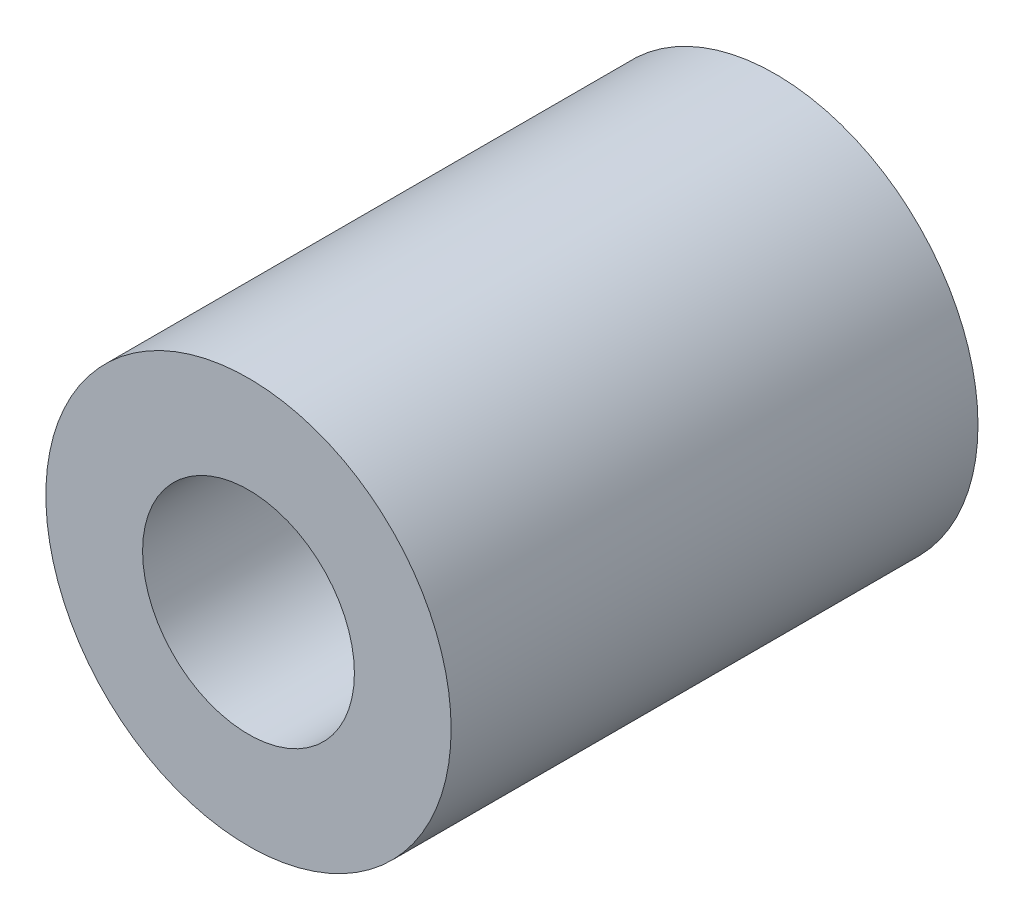
SolidWorks part; units mm, degrees
material "6061-T6 (SS)"
ref_plane "Front Plane" through (0, 0, 0) normal (0, 0, 1) x (1, 0, 0)
ref_plane "Top Plane" through (0, 0, 0) normal (0, 1, 0) x (1, 0, 0)
ref_plane "Right Plane" through (0, 0, 0) normal (1, 0, 0) x (0, 0, -1)
sketch "Sketch1" plane through (0, 0, 0) normal (0, 0, 1) x (1, 0, 0)
  circle A0 centre (0, 0) radius 4.7625
  circle A1 centre (0, 0) radius 2.4892
  dimension "D1" = 9.525
  dimension "D2" = 4.9784
extrude "Boss-Extrude1" add sketch "Sketch1" along normal mid plane 12.3825
